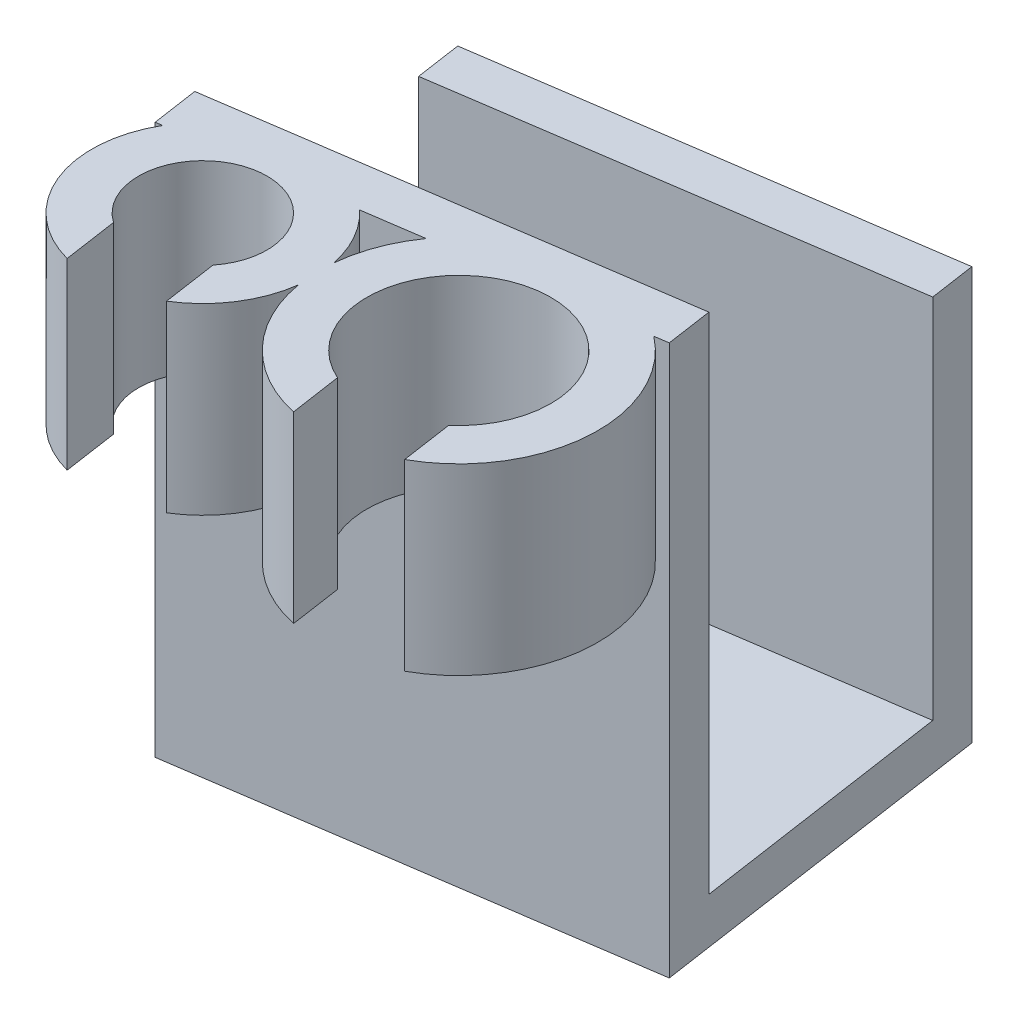
SolidWorks part; units mm, degrees
ref_plane "Front Plane" through (0, 0, 0) normal (0, 0, 1) x (1, 0, 0)
ref_plane "Top Plane" through (0, 0, 0) normal (0, 1, 0) x (1, 0, 0)
ref_plane "Right Plane" through (0, 0, 0) normal (1, 0, 0) x (0, 0, -1)
sketch "Sketch1" plane through (0, 0, 0) normal (0, 1, 0) x (1, 0, 0)
  circle A0 centre (0, 0) radius 4.5085
  arc A1 (7.527, 1.5426) -> (7.6195, -0.99) centre (0, 0) ccw
  circle A2 centre (17.1097, 0.6243) radius 6.4516
  arc A3 (7.6195, -0.99) -> (7.527, 1.5426) centre (17.1097, 0.6243) ccw
  dimension "D1" = 3.175
  dimension "D2" = 9.017
  dimension "D3" = 12.9032
  dimension "D4" = 3.175
extrude "Boss-Extrude1" add sketch "Sketch1" along normal blind 12.7 contours A1 A3
sketch "Sketch2" plane through (0, 0, 0) normal (0, -1, 0) x (1, 0, 0)
  circle A0 centre (0, 0) radius 4.445
  circle A1 centre (17.1097, -0.6243) radius 6.3754
  dimension "D1" = 8.89
  dimension "D2" = 12.7508
extrude "Cut-Extrude1" cut sketch "Sketch2" against normal through all
sketch "Sketch3" plane through (0, 12.7, 0) normal (0, 1, 0) x (1, 0, 0)
  line L16 (-7.5723, 7.0137) -> (23.4702, 11.584)
  line L17 (23.4702, 11.584) -> (23.9438, 8.3676)
  line L18 (-7.5723, 7.0137) -> (-7.0987, 3.7972)
  line L19 (-7.0987, 3.7972) -> (23.9438, 8.3676)
extrude "Boss-Extrude2" add sketch "Sketch3" against normal blind 38.1
ref_plane "Plane1" through (-1.1714, 0, -7.9561) normal (-0.1457, 0, -0.9893) x (-0.9893, 0, 0.1457)
sketch "Sketch6" plane through (-1.1714, 0, -7.9561) normal (-0.1457, 0, -0.9893) x (-0.9893, 0, 0.1457)
  line L0 (6.4699, -25.4) -> (6.4699, -22.225)
  line L1 (6.4699, -25.4) -> (6.4699, 12.7) construction
  line L2 (6.4699, -22.225) -> (-24.9072, -22.225)
  line L3 (-24.9072, -25.4) -> (-24.9072, 12.7) construction
  line L4 (-24.9072, -22.225) -> (-24.9072, -25.4)
  line L5 (-24.9072, -25.4) -> (6.4699, -25.4)
  dimension "D1" = 3.175
extrude "Boss-Extrude5" add sketch "Sketch6" along normal blind 21.59
ref_plane "Plane2" through (0, -22.225, 0) normal (0, 1, 0) x (1, 0, 0)
sketch "Sketch7" plane through (0, -22.225, 0) normal (0, 1, 0) x (1, 0, 0)
  line L0 (-10.717, 28.3734) -> (-10.2496, 25.1984)
  line L1 (-10.717, 28.3734) -> (-7.5723, 7.0137) construction
  line L2 (-10.2496, 25.1984) -> (20.7929, 29.7688)
  line L3 (20.3255, 32.9438) -> (23.4702, 11.584) construction
  line L4 (20.7929, 29.7688) -> (20.3255, 32.9438)
  line L5 (20.3255, 32.9438) -> (-10.717, 28.3734)
  dimension "D1" = 3.175
extrude "Boss-Extrude6" add sketch "Sketch7" along normal blind 25.4
ref_plane "Plane3" through (0, 12.7, 0) normal (0, 1, 0) x (1, 0, 0)
sketch "Sketch8" plane through (0, 12.7, 0) normal (0, 1, 0) x (1, 0, 0)
  line L0 (0, 0) -> (-1.1714, 7.9561) construction
  line L1 (23.4702, 11.584) -> (-7.5723, 7.0137) construction
  line L2 (-1.1714, 7.9561) -> (1.2594, -8.5543) construction
  line L3 (17.1097, 0.6243) -> (15.6653, 10.4349) construction
  line L4 (15.6653, 10.4349) -> (18.6039, -9.5241) construction
  line L5 (-2.5282, -3.656) -> (3.4746, -2.7722)
  line L6 (3.4746, -2.7722) -> (4.3268, -8.5606)
  line L7 (4.3268, -8.5606) -> (-1.676, -9.4443)
  line L8 (-1.676, -9.4443) -> (-2.5282, -3.656)
  line L13 (14.5424, -5.2113) -> (21.25, -4.2238)
  line L14 (21.25, -4.2238) -> (21.9577, -9.0303)
  line L15 (21.9577, -9.0303) -> (15.25, -10.0179)
  line L16 (14.5424, -5.2113) -> (15.25, -10.0179)
  circle A0 centre (0, 0) radius 4.445 construction
  circle A2 centre (17.1097, 0.6243) radius 6.3754 construction
  point P23 (17.8962, -4.7176)
extrude "Cut-Extrude3" cut sketch "Sketch8" against normal through all
